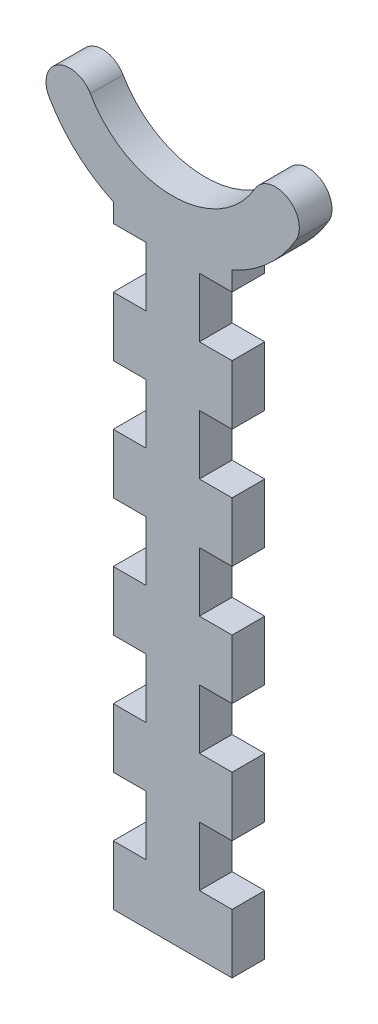
SolidWorks part; units mm, degrees
material "ﾁｰｸ材"
ref_plane "正面" through (0, 0, 0) normal (0, 0, 1) x (1, 0, 0)
ref_plane "平面" through (0, 0, 0) normal (0, 1, 0) x (1, 0, 0)
ref_plane "右側面" through (0, 0, 0) normal (1, 0, 0) x (0, 0, -1)
sketch "ｽｹｯﾁ1" plane through (0, 0, 0) normal (0, 0, 1) x (1, 0, 0)
  line L0 (-10, -21.8174) -> (-10, -125)
  line L1 (-10, -125) -> (10, -125)
  line L2 (10, -125) -> (10, -21.8174)
  arc A0 (-13.8564, -8) -> (13.8564, -8) centre (0, 0) ccw
  arc A1 (13.8564, -8) -> (20.7846, -12) centre (17.3205, -10) cw
  arc A2 (20.7846, -12) -> (10, -21.8174) centre (0, 0) cw
  arc A3 (-20.7846, -12) -> (-13.8564, -8) centre (-17.3205, -10) cw
  arc A4 (-10, -21.8174) -> (-20.7846, -12) centre (0, 0) cw
  point P9 (0, -125)
  dimension "D1" = 16
  dimension "D2" = 24
  dimension "D3" = 120
  dimension "D5" = 20
  dimension "D4" = 125
extrude "ﾎﾞｽ - 押し出し1" add sketch "ｽｹｯﾁ1" along normal blind 5.5
sketch "ｽｹｯﾁ2" plane through (0, 0, 5.5) normal (0, 0, 1) x (1, 0, 0)
  line L0 (-10, -95) -> (-10, -85)
  line L5 (-10, -95) -> (-4.5, -95)
  line L18 (-10, -21.8174) -> (-10, -125) construction
  line L59 (-10, -115) -> (-4.5, -115)
  line L60 (-10, -115) -> (-10, -105)
  line L61 (-10, -105) -> (-4.5, -105)
  line L62 (-4.5, -115) -> (-4.5, -105)
  line L63 (-10, -125) -> (10, -125) construction
  line L64 (-4.5, -95) -> (-4.5, -85)
  line L65 (-10, -85) -> (-4.5, -85)
  line L66 (-10, -75) -> (-10, -65)
  line L67 (-10, -75) -> (-4.5, -75)
  line L68 (-4.5, -75) -> (-4.5, -65)
  line L69 (-10, -65) -> (-4.5, -65)
  line L70 (-10, -55) -> (-10, -45)
  line L71 (-10, -55) -> (-4.5, -55)
  line L72 (-4.5, -55) -> (-4.5, -45)
  line L73 (-10, -45) -> (-4.5, -45)
  line L74 (-10, -35) -> (-10, -25)
  line L75 (-10, -35) -> (-4.5, -35)
  line L76 (-4.5, -35) -> (-4.5, -25)
  line L77 (-10, -25) -> (-4.5, -25)
  line L78 (0, 0) -> (0, -11.9682) construction
  line L79 (10, -105) -> (4.5, -105)
  line L80 (4.5, -115) -> (4.5, -105)
  line L81 (10, -115) -> (4.5, -115)
  line L82 (10, -115) -> (10, -105)
  line L83 (10, -95) -> (4.5, -95)
  line L84 (4.5, -95) -> (4.5, -85)
  line L85 (10, -85) -> (4.5, -85)
  line L86 (10, -95) -> (10, -85)
  line L87 (10, -75) -> (4.5, -75)
  line L88 (4.5, -75) -> (4.5, -65)
  line L89 (10, -65) -> (4.5, -65)
  line L90 (10, -75) -> (10, -65)
  line L91 (10, -55) -> (4.5, -55)
  line L92 (4.5, -55) -> (4.5, -45)
  line L93 (10, -45) -> (4.5, -45)
  line L94 (10, -55) -> (10, -45)
  line L95 (10, -35) -> (4.5, -35)
  line L96 (4.5, -35) -> (4.5, -25)
  line L97 (10, -25) -> (4.5, -25)
  line L98 (10, -35) -> (10, -25)
  dimension "D1" = 5.5
  dimension "D2" = 10
  dimension "D3" = 10
  dimension "D4" = 5
extrude "ｶｯﾄ - 押し出し1" cut sketch "ｽｹｯﾁ2" against normal through all
